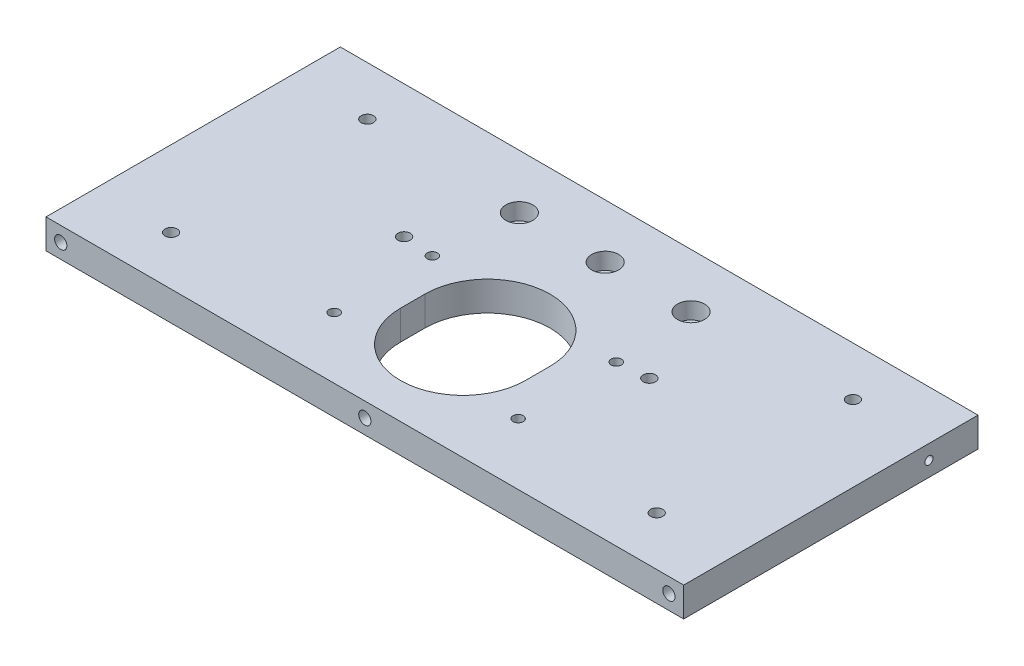
SolidWorks part; units mm, degrees
material "45#"
ref_plane "前视" through (0, 0, 0) normal (0, 0, 1) x (1, 0, 0)
ref_plane "上视" through (0, 0, 0) normal (0, 1, 0) x (1, 0, 0)
ref_plane "右视" through (0, 0, 0) normal (1, 0, 0) x (0, 0, -1)
sketch "草图1" plane through (0, 0, 0) normal (0, 1, 0) x (1, 0, 0)
  line L1 (-130, -60) -> (130, -60)
  line L2 (-130, -60) -> (-130, 60)
  line L3 (-130, 60) -> (130, 60)
  line L4 (130, -60) -> (130, 60)
  line L5 (-130, -60) -> (130, 60) construction
  line L6 (-130, 60) -> (130, -60) construction
  point P0 (0, 0)
  dimension "D1" = 260
  dimension "D2" = 120
extrude "凸台-拉伸1" add sketch "草图1" along normal blind 12
hole_wizard "M6 螺纹孔1" positions "草图3" profile "草图2" tap size "M6" standard "Gb"
sketch "草图3" plane through (0, 0, 60) normal (0, 0, 1) x (1, 0, 0)
  line L0 (0, 12) -> (0, 6) construction
  line L1 (-130, 12) -> (130, 12) construction
  line L2 (0, 6) -> (-130, 6) construction
  line L3 (-130, 12) -> (-130, 0) construction
  point P0 (-124, 6)
  point P15 (0, 6)
  point P20 (124, 6)
  dimension "D1" = 6
sketch "草图2" plane through (-124, 6, 60) normal (1, 0, 0) x (0, -1, 0)
  line L0 (0, 0) -> (0, 16.5022)
  line L1 (0, 16.5022) -> (2.5, 15)
  line L2 (2.5, 15) -> (2.5, 0)
  line L5 (2.5, 0) -> (0, 0)
  line L10 (0, 16.5022) -> (-2.5, 15) construction
  line L11 (0, -6.35) -> (0, 107.95) construction
  dimension "螺纹孔钻头直径" = 5
  dimension "螺纹孔钻头深度" = 15
  dimension "导头角度" = 118
cosmetic thread "孔螺蚊线1" parameters "D1"=12, "D2"=6
cosmetic thread "孔螺蚊线2" parameters "D1"=12, "D2"=6
cosmetic thread "孔螺蚊线3" parameters "D1"=12, "D2"=6
sketch "草图4" plane through (0, 12, 0) normal (0, 1, 0) x (1, 0, 0)
  line L0 (0, -10) -> (0, -20) construction
  line L1 (25.5, -10) -> (25.5, -20)
  line L2 (-25.5, -10) -> (-25.5, -20)
  line L3 (0, 60) -> (0, 39.3018) construction
  line L4 (130, 60) -> (-130, 60) construction
  line L5 (-130, -60) -> (130, -60) construction
  arc A0 (25.5, -10) -> (-25.5, -10) centre (0, -10) ccw
  arc A1 (-25.5, -20) -> (25.5, -20) centre (0, -20) ccw
  point P2 (0, -15)
  dimension "D1" = 51
  dimension "D2" = 10
  dimension "D3" = 45
extrude "切除-拉伸1" cut sketch "草图4" against normal through all
hole_wizard "打孔尺寸根据内六角圆柱头螺钉的类型1" positions "草图6" profile "草图5" counterbore size "M6" standard "Gb" end condition through all
sketch "草图6" plane through (0, 12, 0) normal (0, 1, 0) x (1, 0, 0)
  line L0 (0, 60) -> (0, 39.1103) construction
  line L1 (130, 60) -> (-130, 60) construction
  line L2 (-130, -60) -> (130, -60) construction
  point P0 (-35, 38)
  point P10 (35, 38)
  point P14 (0, 38)
  dimension "D1" = 70
  dimension "D2" = 98
sketch "草图5" plane through (-35, 12, -38) normal (1, 0, 0) x (0, 0, 1)
  line L0 (0, 0) -> (0, 12)
  line L1 (0, 12) -> (3.3, 12)
  line L3 (3.3, 12) -> (3.3, 6.8)
  line L4 (3.3, 6.8) -> (5.5, 6.8)
  line L5 (5.5, 6.8) -> (5.5, 0)
  line L7 (5.5, 0) -> (0, 0)
  line L11 (0, -6.35) -> (0, 107.95) construction
  dimension "通孔孔直径" = 6.6
  dimension "通孔孔深度" = 12
  dimension "柱形沉头孔直径" = 11
  dimension "柱形沉头孔深度" = 6.8
hole_wizard "M6 螺纹孔3" positions "草图8" profile "草图7" tap size "M6" standard "Gb"
sketch "草图8" plane through (0, 0, -60) normal (0, 0, -1) x (-1, 0, 0)
  line L0 (0, 12) -> (0, 6) construction
  line L1 (-130, 12) -> (130, 12) construction
  line L2 (0, 6) -> (130, 6) construction
  line L3 (130, 12) -> (130, 0) construction
  point P0 (20, 6)
  point P13 (-20, 6)
  dimension "D1" = 40
sketch "草图7" plane through (-20, 6, -60) normal (1, 0, 0) x (0, 1, 0)
  line L0 (0, 0) -> (0, 16.5022)
  line L1 (0, 16.5022) -> (2.5, 15)
  line L2 (2.5, 15) -> (2.5, 0)
  line L5 (2.5, 0) -> (0, 0)
  line L10 (0, 16.5022) -> (-2.5, 15) construction
  line L11 (0, -6.35) -> (0, 107.95) construction
  dimension "螺纹孔钻头直径" = 5
  dimension "螺纹孔钻头深度" = 15
  dimension "导头角度" = 118
cosmetic thread "孔螺蚊线6" parameters "D1"=12, "D2"=6
cosmetic thread "孔螺蚊线7" parameters "D1"=12, "D2"=6
hole_wizard "M5 螺纹孔1" positions "草图10" profile "草图9" tap size "M5" standard "Gb" end condition through all
sketch "草图10" plane through (0, 12, 0) normal (0, 1, 0) x (1, 0, 0)
  line L0 (25.5, -15) -> (0, -15) construction
  line L1 (25.5, -20) -> (25.5, -10) construction
  line L2 (0, -15) -> (0, -45.5) construction
  arc A0 (-25.5, -20) -> (25.5, -20) centre (0, -20) ccw construction
  point P12 (37.5, 5)
  point P15 (37.5, -35)
  point P16 (-37.5, -35)
  point P17 (-37.5, 5)
  dimension "D1" = 40
  dimension "D2" = 75
sketch "草图9" plane through (37.5, 12, -5) normal (1, 0, 0) x (0, 0, 1)
  line L0 (0, 0) -> (0, 12)
  line L1 (0, 12) -> (2.1, 12)
  line L2 (2.1, 12) -> (2.1, 0)
  line L5 (2.1, 0) -> (0, 0)
  line L11 (0, -6.35) -> (0, 107.95) construction
  dimension "通孔螺纹孔钻头直径" = 4.2
  dimension "通孔螺纹孔钻头深度" = 12
cosmetic thread "孔螺蚊线8" parameters "D2"=5
cosmetic thread "孔螺蚊线9" parameters "D2"=5
cosmetic thread "孔螺蚊线10" parameters "D2"=5
cosmetic thread "孔螺蚊线11" parameters "D2"=5
hole_wizard "M6 螺纹孔4" positions "草图12" profile "草图11" tap size "M6" standard "Gb" end condition through all
sketch "草图12" plane through (0, 12, 0) normal (0, 1, 0) x (1, 0, 0)
  line L0 (0, 60) -> (0, 20.1762) construction
  line L1 (130, 60) -> (-130, 60) construction
  line L2 (25.5, -20) -> (25.5, -10) construction
  point P0 (50, 6)
  point P11 (-50, 6)
  point P12 (25.5, -15)
  dimension "D1" = 21
  dimension "D2" = 100
sketch "草图11" plane through (50, 12, -6) normal (1, 0, 0) x (0, 0, 1)
  line L0 (0, 0) -> (0, 12)
  line L1 (0, 12) -> (2.5, 12)
  line L2 (2.5, 12) -> (2.5, 0)
  line L5 (2.5, 0) -> (0, 0)
  line L11 (0, -6.35) -> (0, 107.95) construction
  dimension "通孔螺纹孔钻头直径" = 5
  dimension "通孔螺纹孔钻头深度" = 12
cosmetic thread "孔螺蚊线12" parameters "D2"=6
cosmetic thread "孔螺蚊线13" parameters "D2"=6
hole_wizard "M6 螺纹孔5" positions "草图14" profile "草图13" tap size "M6" standard "Gb"
sketch "草图14" plane through (0, 0, 0) normal (0, -1, 0) x (-1, 0, 0)
  line L0 (0, 60) -> (0, 0) construction
  line L1 (-130, 60) -> (130, 60) construction
  line L2 (0, 0) -> (130, 0) construction
  line L3 (130, 60) -> (130, -60) construction
  point P0 (99, -40)
  point P14 (99, 40)
  point P15 (-99, 40)
  point P16 (-99, -40)
  dimension "D1" = 80
  dimension "D2" = 198
sketch "草图13" plane through (-99, 0, 40) normal (1, 0, 0) x (0, 0, -1)
  line L0 (0, 0) -> (0, 16.5022)
  line L1 (0, 16.5022) -> (2.5, 15)
  line L2 (2.5, 15) -> (2.5, 0)
  line L5 (2.5, 0) -> (0, 0)
  line L10 (0, 16.5022) -> (-2.5, 15) construction
  line L11 (0, -6.35) -> (0, 107.95) construction
  dimension "螺纹孔钻头直径" = 5
  dimension "螺纹孔钻头深度" = 15
  dimension "导头角度" = 118
cosmetic thread "孔螺蚊线14" parameters "D1"=12, "D2"=6
cosmetic thread "孔螺蚊线15" parameters "D1"=12, "D2"=6
cosmetic thread "孔螺蚊线16" parameters "D1"=12, "D2"=6
cosmetic thread "孔螺蚊线17" parameters "D1"=12, "D2"=6
hole_wizard "M4 螺纹孔1" positions "草图16" profile "草图15" tap size "M4" standard "Gb"
sketch "草图16" plane through (-130, 0, 0) normal (-1, 0, 0) x (0, 0, 1)
  line L0 (-45, 6) -> (-60, 6) construction
  line L1 (-60, 12) -> (-60, 0) construction
  point P0 (-40, 6)
  dimension "D1" = 20
sketch "草图15" plane through (-130, 6, -40) normal (0, 1, 0) x (0, 0, 1)
  line L0 (0, 0) -> (0, 11.0914)
  line L1 (0, 11.0914) -> (1.65, 10.1)
  line L2 (1.65, 10.1) -> (1.65, 0)
  line L5 (1.65, 0) -> (0, 0)
  line L10 (0, 11.0914) -> (-1.65, 10.1) construction
  line L11 (0, -6.35) -> (0, 107.95) construction
  dimension "螺纹孔钻头直径" = 3.3
  dimension "螺纹孔钻头深度" = 10.1
  dimension "导头角度" = 118
cosmetic thread "孔螺蚊线18" parameters "D1"=8, "D2"=4
mirror "镜向1" about plane through (0, 0, 0) normal (1, 0, 0) of "M4 螺纹孔1"
